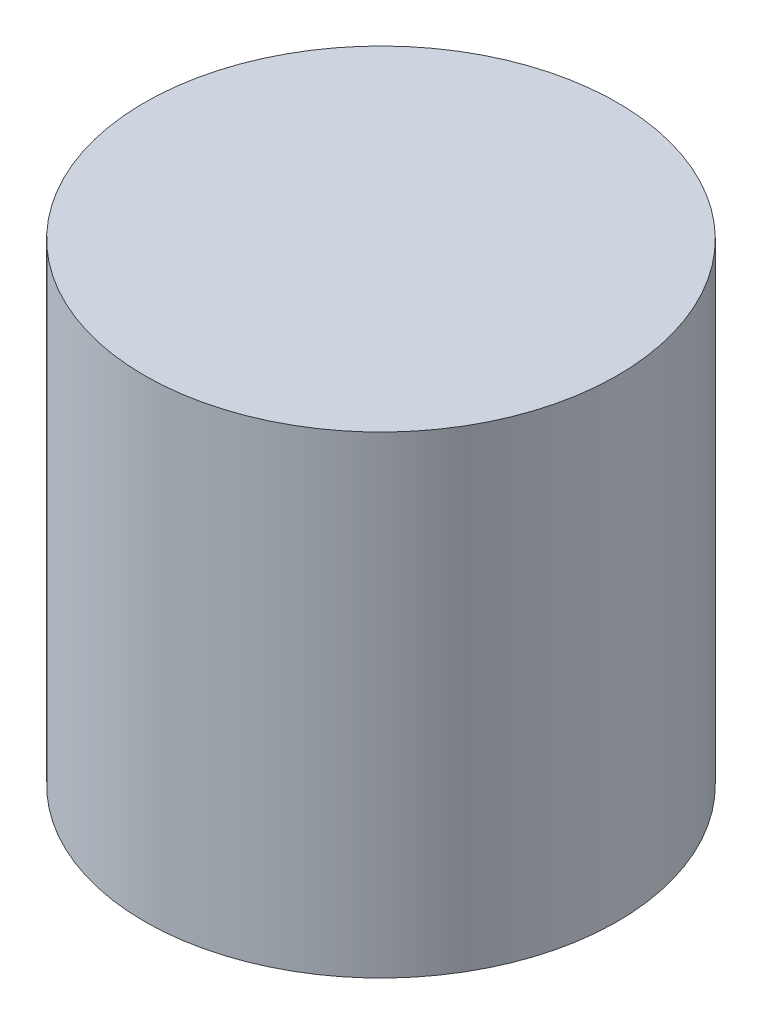
SolidWorks part; units mm, degrees
material "Neodynium"
ref_plane "Front Plane" through (0, 0, 0) normal (0, 0, 1) x (1, 0, 0)
ref_plane "Top Plane" through (0, 0, 0) normal (0, 1, 0) x (1, 0, 0)
ref_plane "Right Plane" through (0, 0, 0) normal (1, 0, 0) x (0, 0, -1)
sketch "Sketch1" plane through (0, 0, 0) normal (0, 1, 0) x (1, 0, 0)
  circle A0 centre (0, 0) radius 0.5
  dimension "D1" = 1
extrude "Boss-Extrude1" add sketch "Sketch1" along normal blind 1
